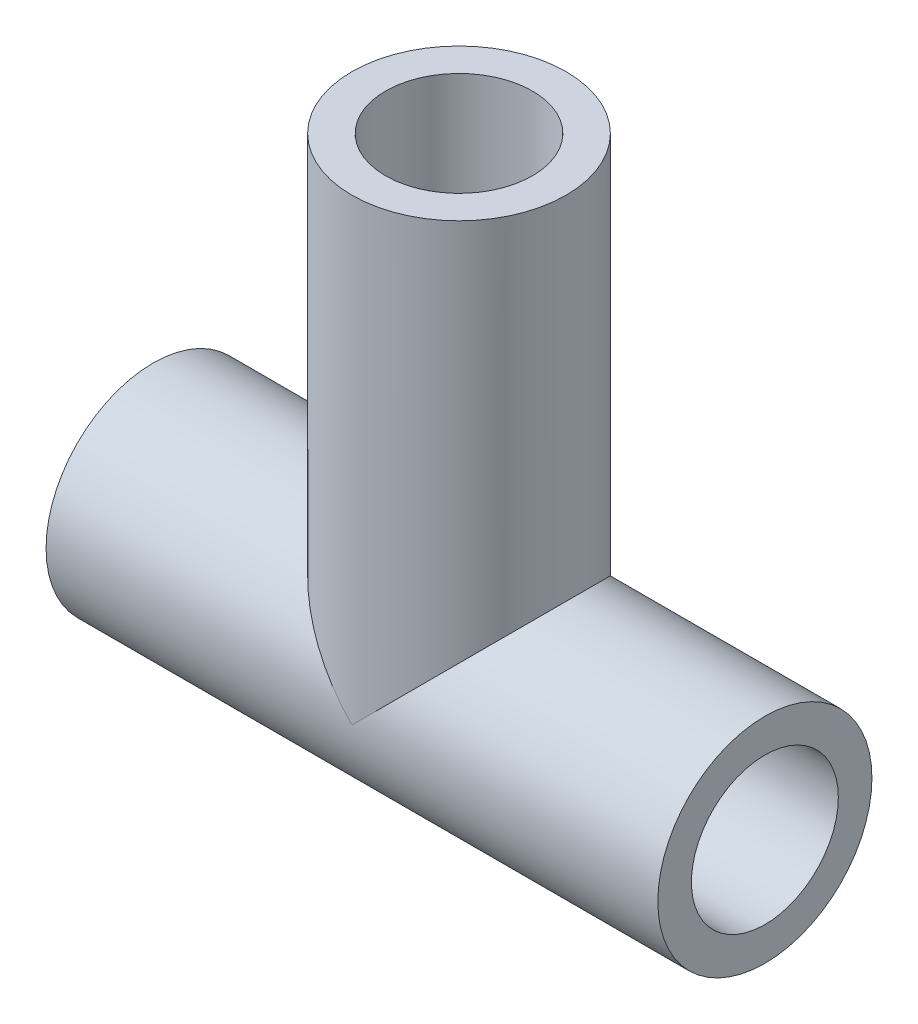
SolidWorks part; units mm, degrees
material "Nylon 101"
ref_plane "Front Plane" through (0, 0, 0) normal (0, 0, 1) x (1, 0, 0)
ref_plane "Top Plane" through (0, 0, 0) normal (0, 1, 0) x (1, 0, 0)
ref_plane "Right Plane" through (0, 0, 0) normal (1, 0, 0) x (0, 0, -1)
sketch "Sketch1" plane through (0, 0, 0) normal (1, 0, 0) x (0, 0, -1)
  circle A0 centre (0, 0) radius 4.445
  dimension "D2" = 8.89
extrude "Boss-Extrude1" add sketch "Sketch1" along normal blind 25.4
sketch "Sketch2" plane through (0, 0, 0) normal (0, 1, 0) x (1, 0, 0)
  circle A1 centre (12.7, 0) radius 4.445
  dimension "D3" = 8.89
  dimension "D1" = 12.7
extrude "Boss-Extrude2" add sketch "Sketch2" along normal blind 19.05
sketch "Sketch3" plane through (25.4, 0, 0) normal (1, 0, 0) x (0, 0, -1)
  circle A0 centre (0, 0) radius 3.05
  dimension "D1" = 6.1
extrude "Cut-Extrude1" cut sketch "Sketch3" against normal through all
sketch "Sketch4" plane through (0, 19.05, 0) normal (0, 1, 0) x (1, 0, 0)
  circle A0 centre (12.7, 0) radius 3.05
  dimension "D1" = 6.1
extrude "Cut-Extrude2" cut sketch "Sketch4" against normal up to next
